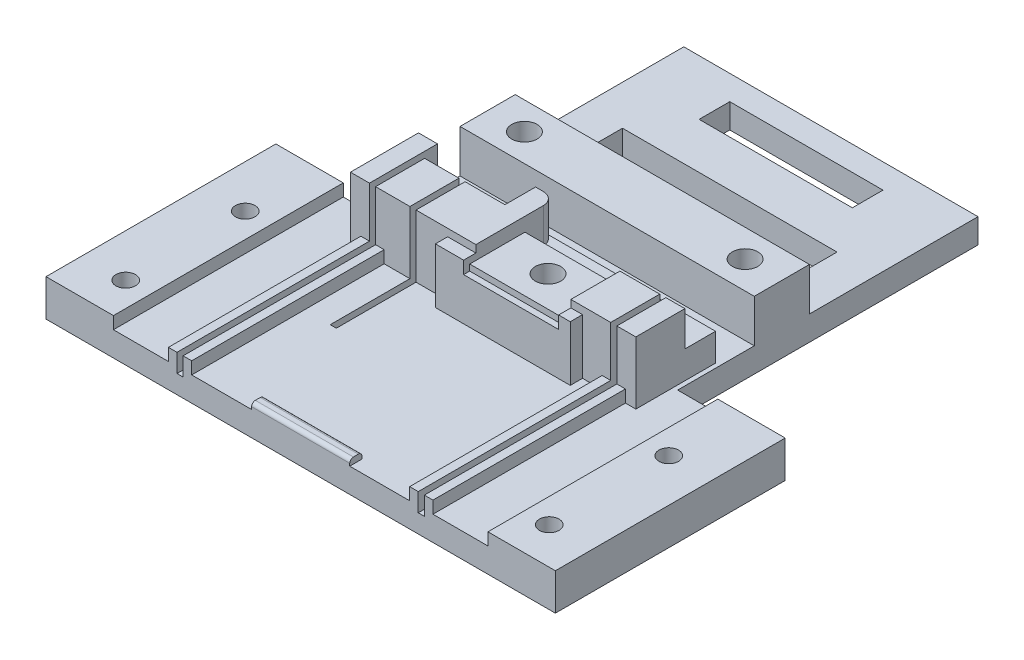
SolidWorks part; units mm, degrees
ref_plane "Front Plane" through (0, 0, 0) normal (0, 0, 1) x (1, 0, 0)
ref_plane "Top Plane" through (0, 0, 0) normal (0, 1, 0) x (1, 0, 0)
ref_plane "Right Plane" through (0, 0, 0) normal (1, 0, 0) x (0, 0, -1)
sketch "Sketch1" plane through (0, 0, 0) normal (0, 1, 0) x (1, 0, 0)
  line L0 (0, 0) -> (0, 37.5)
  line L1 (0, 37.5) -> (17.55, 37.5)
  line L2 (17.55, 37.5) -> (17.55, 86.5)
  line L3 (17.55, 86.5) -> (65.55, 86.5)
  line L4 (65.55, 86.5) -> (65.55, 37.5)
  line L5 (65.55, 37.5) -> (83.1, 37.5)
  line L6 (83.1, 37.5) -> (83.1, 0)
  line L7 (83.1, 0) -> (0, 0)
  line L9 (29.05, 82.5) -> (54.05, 82.5)
  line L10 (29.05, 82.5) -> (29.05, 77.5)
  line L11 (29.05, 77.5) -> (54.05, 77.5)
  line L12 (54.05, 82.5) -> (54.05, 77.5)
  line L13 (24.05, 70) -> (59.05, 70)
  line L14 (24.05, 70) -> (24.05, 59)
  line L15 (24.05, 59) -> (59.05, 59)
  line L16 (59.05, 70) -> (59.05, 59)
  circle A0 centre (7, 25.5) radius 1.6
  circle A1 centre (7, 6) radius 1.6
  circle A2 centre (76.1, 6) radius 1.6
  circle A3 centre (76.1, 25.5) radius 1.6
  point P25 (29.05, 80)
  dimension "D5" = 3.2
  dimension "D1" = 37.5
  dimension "D2" = 49
  dimension "D3" = 17.55
  dimension "D4" = 48
  dimension "D6" = 7
  dimension "D7" = 12
  dimension "D8" = 6
  dimension "D9" = 7
  dimension "D10" = 25
  dimension "D11" = 5
  dimension "D12" = 11.5
  dimension "D13" = 4
  dimension "D14" = 7.5
  dimension "D15" = 11
  dimension "D16" = 35
  dimension "D17" = 6.5
extrude "Boss-Extrude1" add sketch "Sketch1" along normal blind 4
chamfer "Chamfer1" distance 1.4 angle 45 4 edges at (76.1, 0, -23.9) (7, 0, -23.9) (76.1, 0, -4.4) (7, 0, -4.4)
sketch "Sketch2" plane through (0, 4, 0) normal (0, 1, 0) x (1, 0, 0)
  line L0 (17.55, 86.5) -> (17.55, 37.5) construction
  line L1 (17.55, 59) -> (65.55, 59)
  line L2 (17.55, 59) -> (17.55, 50)
  line L3 (17.55, 50) -> (65.55, 50)
  line L4 (65.55, 59) -> (65.55, 50)
  line L5 (65.55, 37.5) -> (65.55, 86.5) construction
  line L6 (24.05, 59) -> (59.05, 59) construction
  circle A0 centre (23.55, 54.5022) radius 2.075
  circle A1 centre (59.55, 54.5022) radius 2.075
  point P14 (0, 0)
  dimension "D5" = 4.15
  dimension "D1" = 9
  dimension "D2" = 6
  dimension "D3" = 4.4978
  dimension "D4" = 6
extrude "Boss-Extrude2" add sketch "Sketch2" along normal blind 7
sketch "Sketch3" plane through (0, 4, 0) normal (0, 1, 0) x (1, 0, 0)
  line L0 (0, 0) -> (83.1, 0) construction
  line L1 (0, 37.5) -> (11, 37.5)
  line L2 (0, 37.5) -> (0, 0)
  line L3 (0, 0) -> (11, 0)
  line L4 (11, 37.5) -> (11, 0)
  line L6 (83.1, 37.5) -> (72.1, 37.5)
  line L7 (83.1, 37.5) -> (83.1, 0)
  line L8 (83.1, 0) -> (72.1, 0)
  line L9 (72.1, 37.5) -> (72.1, 0)
  circle A0 centre (7, 25.5) radius 1.6
  circle A1 centre (7, 6) radius 1.6
  circle A2 centre (76.1, 6) radius 1.6
  circle A3 centre (76.1, 25.5) radius 1.6
  circle A4 centre (7, 25.5) radius 1.6 construction
  circle A5 centre (7, 6) radius 1.6 construction
  circle A6 centre (76.1, 25.5) radius 1.6 construction
  circle A7 centre (76.1, 6) radius 1.6 construction
  dimension "D1" = 11
  dimension "D2" = 11
extrude "Boss-Extrude3" add sketch "Sketch3" along normal blind 2
sketch "Sketch4" plane through (0, 4, 0) normal (0, 1, 0) x (1, 0, 0)
  line L0 (18.27, 42.5) -> (18.27, 31.4)
  line L1 (18.27, 31.4) -> (21.37, 31.4)
  line L2 (21.37, 31.4) -> (21.37, 40.6)
  line L5 (28.97, 31.4) -> (34.13, 31.4)
  line L6 (34.13, 31.4) -> (34.13, 29.4)
  line L7 (34.13, 29.4) -> (56.13, 29.4)
  line L8 (56.13, 29.4) -> (56.13, 31.4)
  line L9 (56.13, 31.4) -> (60.73, 31.4)
  line L10 (60.73, 31.4) -> (60.73, 39.4)
  line L11 (60.73, 39.4) -> (54.23, 39.4)
  line L12 (54.23, 39.4) -> (54.23, 40.6)
  line L13 (54.23, 40.6) -> (61.73, 40.6)
  line L14 (61.73, 40.6) -> (61.73, 31.4)
  line L15 (61.73, 31.4) -> (64.83, 31.4)
  line L16 (64.83, 31.4) -> (64.83, 44.4)
  line L17 (64.83, 44.4) -> (25.1, 44.4)
  line L18 (25.1, 44.4) -> (25.1, 42.5)
  line L19 (25.1, 42.5) -> (18.27, 42.5)
  line L20 (17.55, 50) -> (17.55, 37.5) construction
  line L21 (65.55, 37.5) -> (65.55, 50) construction
  line L22 (17.55, 37.5) -> (11, 37.5) construction
  line L23 (21.37, 40.6) -> (35.47, 40.6)
  line L24 (22.37, 39.4) -> (27.97, 39.4)
  line L25 (22.37, 39.4) -> (22.37, 31.4)
  line L26 (22.37, 31.4) -> (27.97, 31.4)
  line L27 (27.97, 39.4) -> (27.97, 31.4)
  line L28 (35.47, 40.6) -> (35.47, 39.4)
  line L29 (35.47, 39.4) -> (28.97, 39.4)
  line L30 (28.97, 39.4) -> (28.97, 31.4)
  point P26 (14.275, 37.5)
  point P31 (22.37, 35.4)
  dimension "D1" = 0.72
  dimension "D2" = 0.72
  dimension "D3" = 11.1
  dimension "D4" = 6.1
  dimension "D5" = 3.1
  dimension "D6" = 1
  dimension "D7" = 1.2
  dimension "D8" = 1
  dimension "D9" = 6.83
  dimension "D10" = 1.9
  dimension "D11" = 9.2
  dimension "D12" = 5.6
  dimension "D13" = 5.16
  dimension "D14" = 1
  dimension "D15" = 3.1
  dimension "D16" = 1.2
  dimension "D17" = 7.5
  dimension "D18" = 22
  dimension "D19" = 8
  dimension "D20" = 2
  dimension "D21" = 6.5
extrude "Boss-Extrude4" add sketch "Sketch4" along normal blind 10.2
sketch "Sketch5" plane through (0, 4, 0) normal (0, 1, 0) x (1, 0, 0)
  line L0 (11, 0) -> (72.1, 0) construction
  line L1 (21.37, 31.4) -> (19.97, 31.4)
  line L2 (21.37, 31.4) -> (21.37, 0)
  line L3 (21.37, 0) -> (19.97, 0)
  line L4 (19.97, 31.4) -> (19.97, 0)
  line L6 (22.37, 31.4) -> (23.77, 31.4)
  line L7 (22.37, 31.4) -> (22.37, 0)
  line L8 (22.37, 0) -> (23.77, 0)
  line L9 (23.77, 31.4) -> (23.77, 0)
  line L10 (60.73, 31.4) -> (59.33, 31.4)
  line L11 (60.73, 31.4) -> (60.73, 0)
  line L12 (60.73, 0) -> (59.33, 0)
  line L13 (59.33, 31.4) -> (59.33, 0)
  line L14 (61.73, 31.4) -> (63.13, 31.4)
  line L15 (61.73, 31.4) -> (61.73, 0)
  line L16 (61.73, 0) -> (63.13, 0)
  line L17 (63.13, 31.4) -> (63.13, 0)
  dimension "D1" = 1.4
extrude "Boss-Extrude5" add sketch "Sketch5" along normal blind 2
sketch "Sketch7" plane through (0, 4, 0) normal (0, 1, 0) x (1, 0, 0)
  line L0 (28.97, 31.4) -> (28.97, 18.4)
  line L1 (28.97, 18.4) -> (27.97, 18.4)
  line L2 (27.97, 18.4) -> (27.97, 31.4)
  line L6 (60.73, 0) -> (61.73, 0)
  line L7 (61.73, 0) -> (61.73, 40.6)
  line L8 (61.73, 40.6) -> (54.23, 40.6)
  line L9 (54.23, 40.6) -> (54.23, 39.4)
  line L10 (54.23, 39.4) -> (60.73, 39.4)
  line L11 (60.73, 39.4) -> (60.73, 0)
  line L12 (60.73, 0) -> (61.73, 0)
  line L13 (61.73, 0) -> (61.73, 40.6)
  line L14 (61.73, 40.6) -> (54.23, 40.6)
  line L15 (54.23, 40.6) -> (54.23, 39.4)
  line L16 (54.23, 39.4) -> (60.73, 39.4)
  line L17 (60.73, 39.4) -> (60.73, 0)
  line L18 (59.33, 0) -> (59.33, 31.4)
  line L19 (59.33, 31.4) -> (56.13, 31.4)
  line L20 (56.13, 31.4) -> (56.13, 29.4)
  line L21 (56.13, 29.4) -> (34.13, 29.4)
  line L22 (34.13, 29.4) -> (34.13, 31.4)
  line L23 (34.13, 31.4) -> (28.97, 31.4)
  line L24 (28.97, 31.4) -> (28.97, 39.4)
  line L25 (28.97, 39.4) -> (35.47, 39.4)
  line L26 (35.47, 39.4) -> (35.47, 40.6)
  line L27 (35.47, 40.6) -> (21.37, 40.6)
  line L28 (21.37, 40.6) -> (21.37, 0)
  line L29 (21.37, 0) -> (22.37, 0)
  line L30 (22.37, 0) -> (22.37, 39.4)
  line L31 (22.37, 39.4) -> (27.97, 39.4)
  line L32 (27.97, 39.4) -> (27.97, 31.4)
  line L33 (27.97, 31.4) -> (23.77, 31.4)
  line L34 (23.77, 31.4) -> (23.77, 0)
  line L35 (23.77, 0) -> (59.33, 0)
  line L42 (28.97, 31.4) -> (28.97, 39.4)
  line L43 (28.97, 39.4) -> (35.47, 39.4)
  line L44 (35.47, 39.4) -> (35.47, 40.6)
  line L45 (35.47, 40.6) -> (21.37, 40.6)
  line L46 (21.37, 40.6) -> (21.37, 0)
  line L47 (21.37, 0) -> (22.37, 0)
  line L48 (22.37, 0) -> (22.37, 39.4)
  line L49 (22.37, 39.4) -> (27.97, 39.4)
  line L50 (27.97, 39.4) -> (27.97, 31.4)
  point P6 (27.97, 31.8347)
  dimension "D3" = 13
  dimension "D1" = 0
  dimension "D2" = 0
extrude "Cut-Extrude1" cut sketch "Sketch7" against normal blind 1
sketch "Sketch8" plane through (0, 14.2, 0) normal (0, 1, 0) x (1, 0, 0)
  line L0 (35.47, 40.6) -> (35.47, 44.4)
  line L1 (64.83, 44.4) -> (38.73, 44.4)
  line L2 (64.83, 44.4) -> (64.83, 39.4)
  line L3 (64.83, 39.4) -> (38.73, 39.4)
  line L4 (38.73, 44.4) -> (38.73, 39.4)
  line L5 (64.83, 44.4) -> (25.1, 44.4) construction
  line L6 (35.47, 44.4) -> (25.1, 44.4)
  line L7 (25.1, 44.4) -> (25.1, 42.5)
  line L8 (21.37, 40.6) -> (21.37, 42.5)
  line L9 (25.1, 42.5) -> (18.27, 42.5) construction
  line L10 (21.37, 42.5) -> (25.1, 42.5)
  line L11 (21.37, 40.6) -> (35.47, 40.6)
  dimension "D1" = 5
  dimension "D2" = 26.1
extrude "Cut-Extrude2" cut sketch "Sketch8" against normal blind 5.7
sketch "Sketch9" plane through (0, 14.2, 0) normal (0, 1, 0) x (1, 0, 0)
  line L0 (38.73, 39.4) -> (54.23, 39.4) construction
  line L1 (38.73, 39.4) -> (54.23, 39.4)
  line L2 (38.73, 39.4) -> (38.73, 29.4)
  line L3 (38.73, 29.4) -> (54.23, 29.4)
  line L4 (54.23, 39.4) -> (54.23, 29.4)
  line L5 (34.13, 29.4) -> (56.13, 29.4) construction
  line L6 (34.13, 31.4) -> (34.13, 29.4) construction
  dimension "D1" = 15.5
  dimension "D2" = 4.6
extrude "Cut-Extrude3" cut sketch "Sketch9" against normal blind 2.25
sketch "Sketch10" plane through (0, 14.2, 0) normal (0, 1, 0) x (1, 0, 0)
  line L0 (34.13, 29.4) -> (56.13, 29.4) construction
  line L1 (34.13, 31.4) -> (38.73, 31.4)
  line L2 (34.13, 31.4) -> (34.13, 29.4)
  line L3 (34.13, 29.4) -> (38.73, 29.4)
  line L4 (38.73, 31.4) -> (38.73, 29.4)
  line L5 (38.73, 44.4) -> (38.73, 29.4) construction
  line L7 (54.23, 29.4) -> (56.13, 29.4)
  line L8 (54.23, 29.4) -> (54.23, 31.4)
  line L9 (54.23, 31.4) -> (56.13, 31.4)
  line L10 (56.13, 29.4) -> (56.13, 31.4)
extrude "Cut-Extrude4" cut sketch "Sketch10" against normal blind 1.2
sketch "Sketch11" plane through (0, 11.95, 0) normal (0, 1, 0) x (1, 0, 0)
  line L1 (38.73, 29.4) -> (54.23, 29.4)
  line L2 (38.73, 29.4) -> (38.73, 30.4)
  line L3 (38.73, 30.4) -> (54.23, 30.4)
  line L4 (54.23, 29.4) -> (54.23, 30.4)
  line L5 (54.23, 29.4) -> (54.23, 39.4) construction
  point P7 (0, 0)
  dimension "D1" = 1
extrude "Cut-Extrude5" cut sketch "Sketch11" against normal blind 1
sketch "Sketch12" plane through (0, 11.95, 0) normal (0, 1, 0) x (1, 0, 0)
  line L0 (54.23, 31.4) -> (54.23, 39.4) construction
  line L2 (38.73, 39.4) -> (54.23, 39.4) construction
  circle A0 centre (46.5, 35.4) radius 2.075
  dimension "D1" = 4.15
  dimension "D2" = 7.73
  dimension "D3" = 4
extrude "Cut-Extrude6" cut sketch "Sketch12" against normal blind 7
fillet "Fillet1" radius 2 1 edges at (38.73, 11.35, -44.4)
sketch "Sketch13" plane through (0, 0, -44.4) normal (0, 0, -1) x (-1, 0, 0)
  line L0 (-58.73, 8.5) -> (-58.73, 5.57)
  line L1 (-58.73, 8.5) -> (-56.03, 8.5)
  line L2 (-64.83, 8.5) -> (-36.73, 8.5) construction
  line L3 (-56.03, 8.5) -> (-56.03, 5.57)
  line L4 (-33.57, 8.5) -> (-33.57, 6.8)
  line L5 (-35.47, 8.5) -> (-25.1, 8.5) construction
  line L6 (-30.87, 8.5) -> (-30.87, 6.8)
  line L7 (-33.57, 8.5) -> (-30.87, 8.5)
  line L8 (-26.49, 5.57) -> (-26.49, 8.5)
  line L9 (-26.49, 8.5) -> (-23.79, 8.5)
  line L10 (-25.1, 8.5) -> (-21.37, 8.5) construction
  line L11 (-23.79, 8.5) -> (-23.79, 5.57)
  line L12 (-64.83, 8.5) -> (-64.83, 4) construction
  arc A0 (-58.73, 5.57) -> (-56.03, 5.57) centre (-57.38, 5.57) ccw
  arc A1 (-33.57, 6.8) -> (-30.87, 6.8) centre (-32.22, 6.8) ccw
  arc A2 (-26.49, 5.57) -> (-23.79, 5.57) centre (-25.14, 5.57) ccw
  point P24 (0, 0)
  point P25 (0, 0)
  point P26 (0, 0)
  point P27 (0, 0)
  point P28 (0, 0)
  point P29 (0, 0)
  dimension "D1" = 2.7
  dimension "D2" = 2.7
  dimension "D3" = 2.7
  dimension "D4" = 2.93
  dimension "D5" = 1.7
  dimension "D6" = 2.93
  dimension "D7" = 6.1
  dimension "D8" = 22.46
  dimension "D9" = 4.38
extrude "Cut-Extrude7" cut sketch "Sketch13" against normal up to next
sketch "Sketch14" plane through (0, 4, 0) normal (0, 1, 0) x (1, 0, 0)
  line L0 (23.77, 0) -> (59.33, 0) construction
  line L1 (33.55, 0) -> (49.55, 0)
  line L2 (33.55, 0) -> (33.55, 2)
  line L3 (33.55, 2) -> (49.55, 2)
  line L4 (49.55, 0) -> (49.55, 2)
  line L5 (23.77, 0) -> (23.77, 31.4) construction
  dimension "D1" = 16
  dimension "D2" = 9.78
  dimension "D3" = 2
extrude "Boss-Extrude6" add sketch "Sketch14" along normal blind 1
fillet "Fillet2" radius 0.6 2 edges at (41.55, 5, -2) (41.55, 5, 0)
